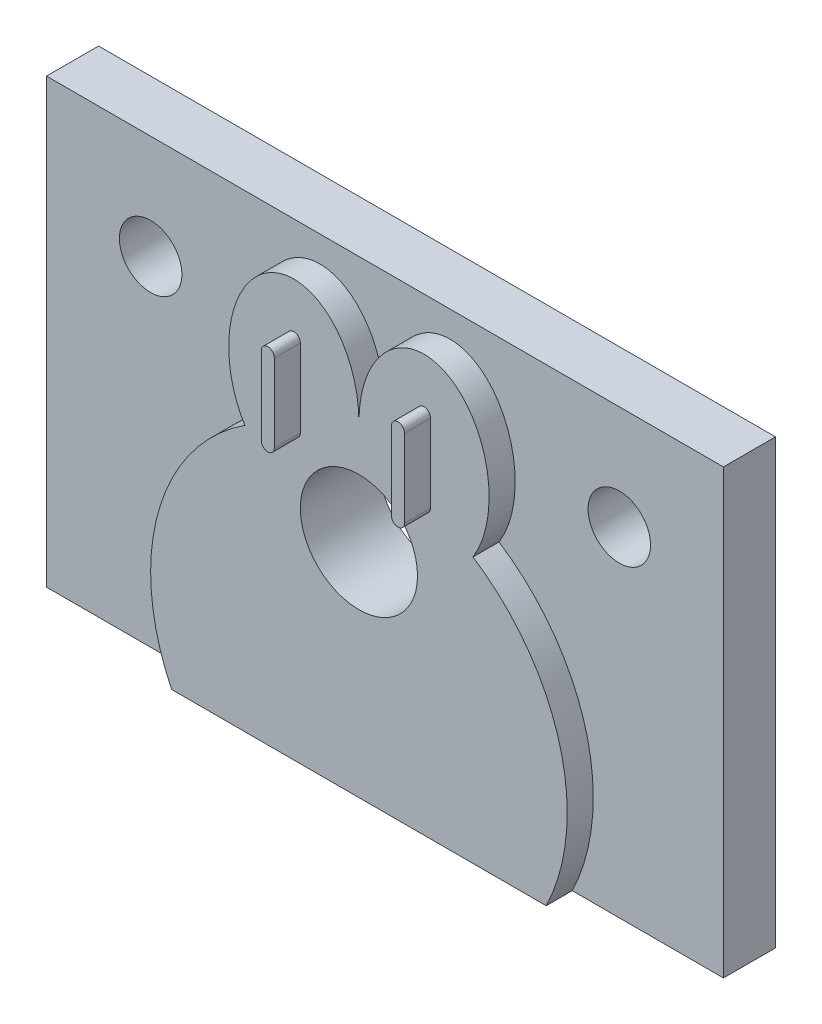
SolidWorks part; units mm, degrees
material "ABS"
ref_plane "正面" through (0, 0, 0) normal (0, 0, 1) x (1, 0, 0)
ref_plane "平面" through (0, 0, 0) normal (0, 1, 0) x (1, 0, 0)
ref_plane "右側面" through (0, 0, 0) normal (1, 0, 0) x (0, 0, -1)
sketch "ｽｹｯﾁ1" plane through (0, 0, 0) normal (0, 0, 1) x (1, 0, 0)
  line L0 (0, 8.5) -> (0, -8.5) construction
  line L1 (13, -8.5) -> (-13, -8.5) construction
  line L2 (13, -8.5) -> (13, 8.5) construction
  line L3 (13, 8.5) -> (-13, 8.5) construction
  line L4 (-13, -8.5) -> (-13, 8.5) construction
  line L5 (13, -8.5) -> (-13, 8.5) construction
  line L6 (13, 8.5) -> (-13, -8.5) construction
  line L7 (-7.1937, -8.5) -> (7.1937, -8.5)
  arc A1 (-7.1937, -8.5) -> (-4.3807, 1.694) centre (0, -5) cw
  arc A3 (4.3807, 1.694) -> (7.1937, -8.5) centre (0, -5) cw
  ellipse E0 centre (-2.5, 4) end of major axis (-2.5, 0.5) minor radius 2.5 (0, 4) -> (-4.3807, 1.694) ccw
  ellipse E1 centre (2.5, 4) end of major axis (2.5, 0.5) minor radius 2.5 (4.3807, 1.694) -> (0, 4) ccw
  point P0 (0, 0)
  point P9 (0, 0)
  dimension "D3" = 8
  dimension "D4" = 8
  dimension "D5" = 5
  dimension "D1" = 17
  dimension "D2" = 26
  dimension "D6" = 5
  dimension "D7" = 3.5
  dimension "D8" = 7
  dimension "D9" = 5
  dimension "D10" = 12.5
  dimension "D11" = 12.5
  dimension "D12" = 3.5
extrude "ﾎﾞｽ - 押し出し1" add sketch "ｽｹｯﾁ1" along normal blind 1
sketch "ｽｹｯﾁ2" plane through (0, 0, 1) normal (0, 0, 1) x (1, 0, 0)
  line L0 (-2.5, 7.5) -> (-2.5, -8.5) construction
  line L1 (-7.1937, -8.5) -> (7.1937, -8.5) construction
  line L2 (-2.5, -8.5) -> (2.5, 7.5) construction
  line L3 (2.5, 7.5) -> (2.5, -8.5) construction
  line L4 (2.5, -8.5) -> (-2.5, 7.5) construction
  line L5 (-5, 4) -> (5, 4) construction
  line L6 (-2.5, 2.5) -> (-2.5, 5.5) construction
  line L7 (-2.75, 2.5) -> (-2.75, 5.5)
  line L8 (-2.25, 2.5) -> (-2.25, 5.5)
  line L9 (2.5, 2.5) -> (2.5, 5.5) construction
  line L10 (2.25, 2.5) -> (2.25, 5.5)
  line L11 (2.75, 2.5) -> (2.75, 5.5)
  circle A0 centre (0, 0) radius 2.25
  arc A1 (-2.75, 2.5) -> (-2.25, 2.5) centre (-2.5, 2.5) ccw
  arc A2 (-2.25, 5.5) -> (-2.75, 5.5) centre (-2.5, 5.5) ccw
  arc A3 (2.25, 2.5) -> (2.75, 2.5) centre (2.5, 2.5) ccw
  arc A4 (2.75, 5.5) -> (2.25, 5.5) centre (2.5, 5.5) ccw
  ellipse E0 centre (-2.5, 4) end of major axis (-2.5, 0.5) minor radius 2.5 (0, 4) -> (-4.3807, 1.694) ccw construction
  ellipse E1 centre (2.5, 4) end of major axis (2.5, 0.5) minor radius 2.5 (4.3807, 1.694) -> (0, 4) ccw construction
  point P23 (-2.5, 4)
  point P26 (2.5, 4)
  point P29 (-2.5, 4)
  point P35 (2.5, 4)
  dimension "D1" = 4.5
  dimension "D5" = 0.25
  dimension "D6" = 0.25
  dimension "D2" = 2.5
  dimension "D3" = 5
  dimension "D4" = 4
  dimension "D7" = 3
  dimension "D8" = 3
extrude "ﾎﾞｽ - 押し出し2" add sketch "ｽｹｯﾁ2" along normal blind 1
sketch "ｽｹｯﾁ3" plane through (0, 0, 0) normal (0, 0, -1) x (-1, 0, 0)
  line L0 (-5, 4) -> (5, 4) construction
  line L1 (-2.5, 7.5) -> (-2.5, 4) construction
  line L2 (2.5, 7.5) -> (2.5, 4) construction
  line L3 (7.1937, -8.5) -> (-7.1937, -8.5) construction
  arc A0 (2.4496, -0.4995) -> (2.4493, 0.5007) centre (0, 0) ccw
  arc A1 (-4.8774, 0.6975) -> (-4.0831, 1.2911) centre (0, -5) cw
  arc A4 (4.0831, 1.2911) -> (4.8774, 0.6975) centre (0, -5) cw
  arc A5 (-2.4493, 0.5007) -> (-2.4496, -0.4995) centre (0, 0) ccw
  ellipse E0 centre (-2.5, 4) end of major axis (-2.5, 0.5) minor radius 2.5 (0, 4) -> (-4.3807, 1.694) ccw construction
  ellipse E1 centre (2.5, 4) end of major axis (2.5, 0.5) minor radius 2.5 (4.3807, 1.694) -> (0, 4) ccw construction
  ellipse E2 centre (-2.5, 4) end of major axis (-2.5, 8.5) minor radius 3.5 (-4.8774, 0.6975) -> (-2.4496, -0.4995) ccw
  ellipse E3 centre (2.5, 4) end of major axis (2.5, 0.5) minor radius 2.5 (2.4493, 0.5007) -> (4.0831, 1.2911) ccw
  ellipse E5 centre (2.5, 4) end of major axis (2.5, -0.5) minor radius 3.5 (2.4496, -0.4995) -> (4.8774, 0.6975) ccw
  ellipse E6 centre (-2.5, 4) end of major axis (-2.5, 0.5) minor radius 2.5 (-4.0831, 1.2911) -> (-2.4493, 0.5007) ccw
  point P49 (-2.5, -1.4711)
  dimension "D1" = 5
  dimension "D6" = 15
  dimension "D9" = 7.5
  dimension "D2" = 4
  dimension "D3" = 2.5
  dimension "D4" = 5
  dimension "D5" = 3.5
  dimension "D7" = 5
  dimension "D8" = 4.5
  dimension "D10" = 3.5
  dimension "D11" = 4.5
  dimension "D12" = 3.5
extrude "ｶｯﾄ - 押し出し1" [suppressed] cut sketch "ｽｹｯﾁ3" against normal through all
sketch "ｽｹｯﾁ4" plane through (0, 0, 0) normal (0, 0, -1) x (-1, 0, 0)
  line L0 (-13, 4.5) -> (13, 4.5) construction
  line L1 (13, 8.5) -> (-13, 8.5)
  line L2 (13, 8.5) -> (13, -8.5)
  line L3 (13, -8.5) -> (-13, -8.5)
  line L4 (-13, 8.5) -> (-13, -8.5)
  line L5 (13, 8.5) -> (-13, -8.5) construction
  line L6 (13, -8.5) -> (-13, 8.5) construction
  circle A0 centre (-9, 4.5) radius 1.2
  circle A1 centre (9, 4.5) radius 1.2
  point P0 (0, 0)
  dimension "D3" = 4
  dimension "D4" = 2.4
  dimension "D5" = 2.4
  dimension "D6" = 4
  dimension "D1" = 17
  dimension "D2" = 26
  dimension "D7" = 4
extrude "ﾎﾞｽ - 押し出し3" add sketch "ｽｹｯﾁ4" along normal blind 2
sketch "ｽｹｯﾁ5" plane through (0, 0, 2) normal (0, 0, 1) x (1, 0, 0)
  circle A0 centre (0, 0) radius 2.25
extrude "ｶｯﾄ - 押し出し2" cut sketch "ｽｹｯﾁ5" against normal through all
